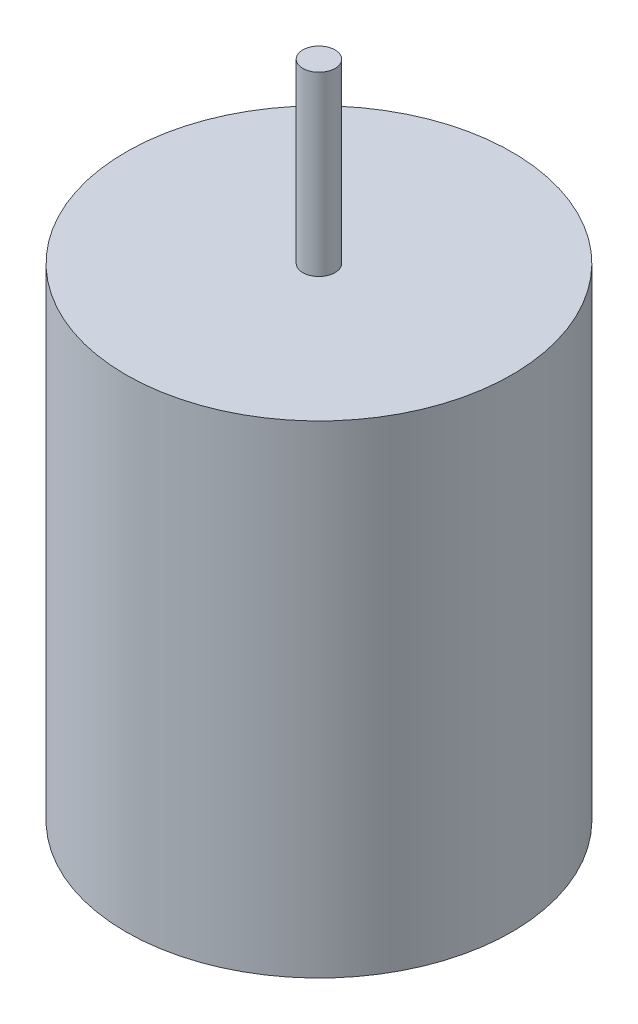
SolidWorks part; units mm, degrees
ref_plane "Front Plane" through (0, 0, 0) normal (0, 0, 1) x (1, 0, 0)
ref_plane "Top Plane" through (0, 0, 0) normal (0, 1, 0) x (1, 0, 0)
ref_plane "Right Plane" through (0, 0, 0) normal (1, 0, 0) x (0, 0, -1)
sketch "Sketch1" plane through (0, 0, 0) normal (0, 1, 0) x (1, 0, 0)
  circle A0 centre (0, 0) radius 12
  dimension "D1" = 24
extrude "Boss-Extrude1" add sketch "Sketch1" along normal blind 30
sketch "Sketch2" plane through (0, 30, 0) normal (0, 1, 0) x (1, 0, 0)
  circle A0 centre (0, 0) radius 1
  dimension "D1" = 2
extrude "Boss-Extrude2" add sketch "Sketch2" along normal blind 11
